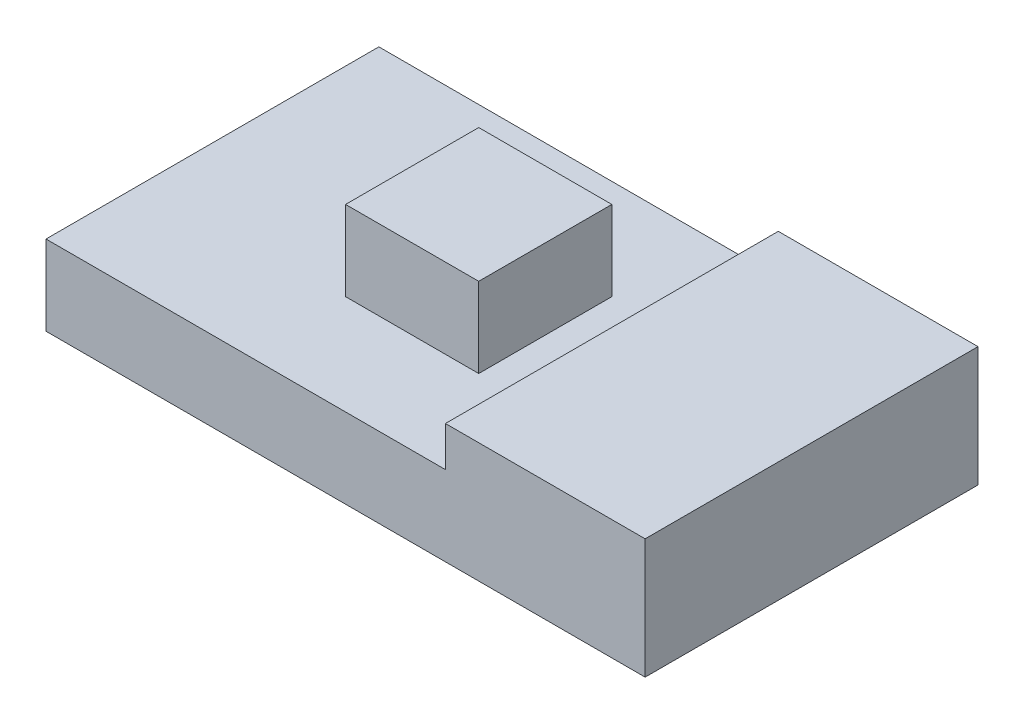
SolidWorks part; units mm, degrees
material "PVC Rigid"
ref_plane "Front Plane" through (0, 0, 0) normal (0, 0, 1) x (1, 0, 0)
ref_plane "Top Plane" through (0, 0, 0) normal (0, 1, 0) x (1, 0, 0)
ref_plane "Right Plane" through (0, 0, 0) normal (1, 0, 0) x (0, 0, -1)
sketch "Sketch6" plane through (0, 0, 0) normal (0, 1, 0) x (1, 0, 0)
  line L1 (-15.9091, 12.5) -> (14.0909, 12.5)
  line L2 (-15.9091, 12.5) -> (-15.9091, -12.5)
  line L3 (-15.9091, -12.5) -> (14.0909, -12.5)
  line L4 (14.0909, 12.5) -> (14.0909, -12.5)
  dimension "D1" = 25
  dimension "D2" = 30
extrude "Boss-Extrude6" add sketch "Sketch6" along normal blind 6
sketch "Sketch7" plane through (0, 6, 0) normal (0, 1, 0) x (1, 0, 0)
  line L0 (-0.9091, 12.5) -> (-0.9091, -12.5)
  line L1 (14.0909, 12.5) -> (-15.9091, 12.5) construction
  line L2 (-15.9091, -12.5) -> (14.0909, -12.5) construction
  line L3 (-0.9091, -12.5) -> (14.0909, -12.5)
  line L4 (14.0909, -12.5) -> (14.0909, 12.5)
  line L5 (14.0909, 12.5) -> (-0.9091, 12.5)
extrude "Boss-Extrude7" add sketch "Sketch7" along normal blind 3
sketch "Sketch8" plane through (0, 6, 0) normal (0, 1, 0) x (1, 0, 0)
  line L0 (-15.9091, 12.5) -> (-15.9091, -12.5) construction
  line L1 (-15.9091, 5) -> (-5.9091, 5)
  line L2 (-15.9091, 5) -> (-15.9091, -5)
  line L3 (-15.9091, -5) -> (-5.9091, -5)
  line L4 (-5.9091, 5) -> (-5.9091, -5)
  point P4 (-15.9091, 0)
  dimension "D1" = 10
  dimension "D2" = 10
extrude "Boss-Extrude8" add sketch "Sketch8" along normal blind 6
sketch "Sketch9" plane through (-15.9091, 0, 0) normal (-1, 0, 0) x (0, 0, 1)
  line L0 (-12.5, 6) -> (-12.5, 0)
  line L1 (-12.5, 0) -> (12.5, 0)
  line L2 (12.5, 0) -> (12.5, 6)
  line L3 (12.5, 6) -> (-12.5, 6)
extrude "Boss-Extrude9" add sketch "Sketch9" along normal blind 15
